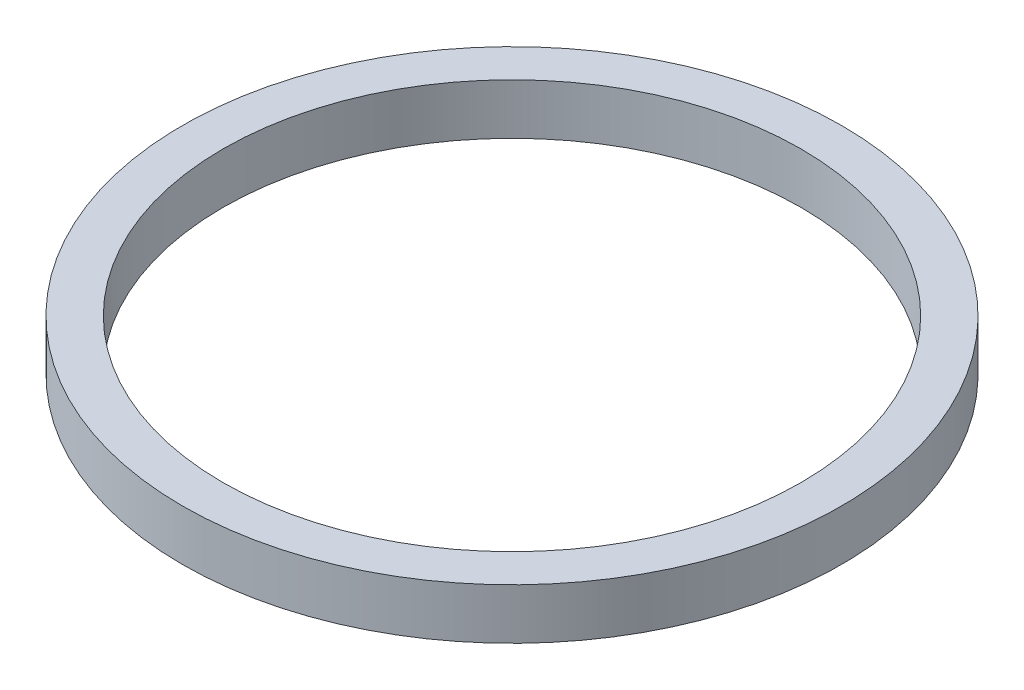
SolidWorks part; units mm, degrees
ref_plane "Front Plane" through (0, 0, 0) normal (0, 0, 1) x (1, 0, 0)
ref_plane "Top Plane" through (0, 0, 0) normal (0, 1, 0) x (1, 0, 0)
ref_plane "Right Plane" through (0, 0, 0) normal (1, 0, 0) x (0, 0, -1)
sketch "Sketch1" plane through (0, 0, 0) normal (0, 1, 0) x (1, 0, 0)
  circle A0 centre (0, 0) radius 20.6375
  circle A1 centre (0, 0) radius 18.0975
  dimension "D1" = 41.275
  dimension "D2" = 2.54
extrude "Boss-Extrude1" add sketch "Sketch1" along normal blind 3.175
